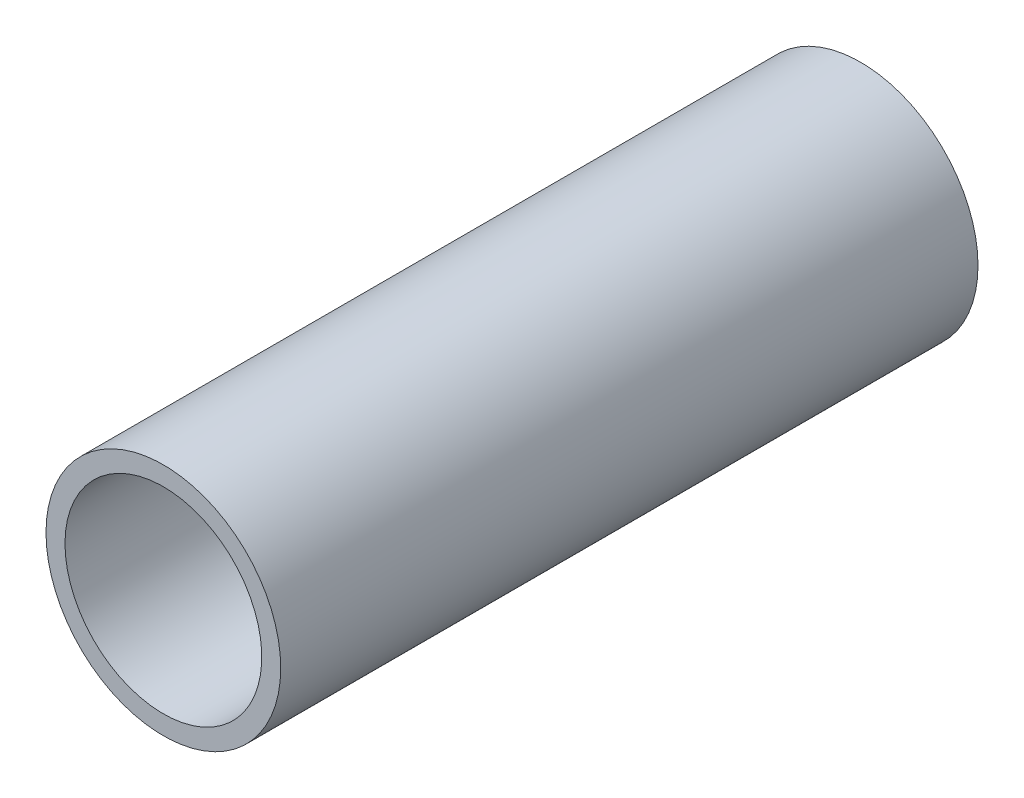
SolidWorks part; units mm, degrees
ref_plane "Front Plane" through (0, 0, 0) normal (0, 0, 1) x (1, 0, 0)
ref_plane "Top Plane" through (0, 0, 0) normal (0, 1, 0) x (1, 0, 0)
ref_plane "Right Plane" through (0, 0, 0) normal (1, 0, 0) x (0, 0, -1)
sketch "Sketch1" plane through (0, 0, 0) normal (0, 0, 1) x (1, 0, 0)
  circle A0 centre (0, 0) radius 30.3
  circle A1 centre (0, 0) radius 25.4
  dimension "D1" = 60.6
  dimension "D2" = 50.8
extrude "Boss-Extrude1" add sketch "Sketch1" along normal blind 180
